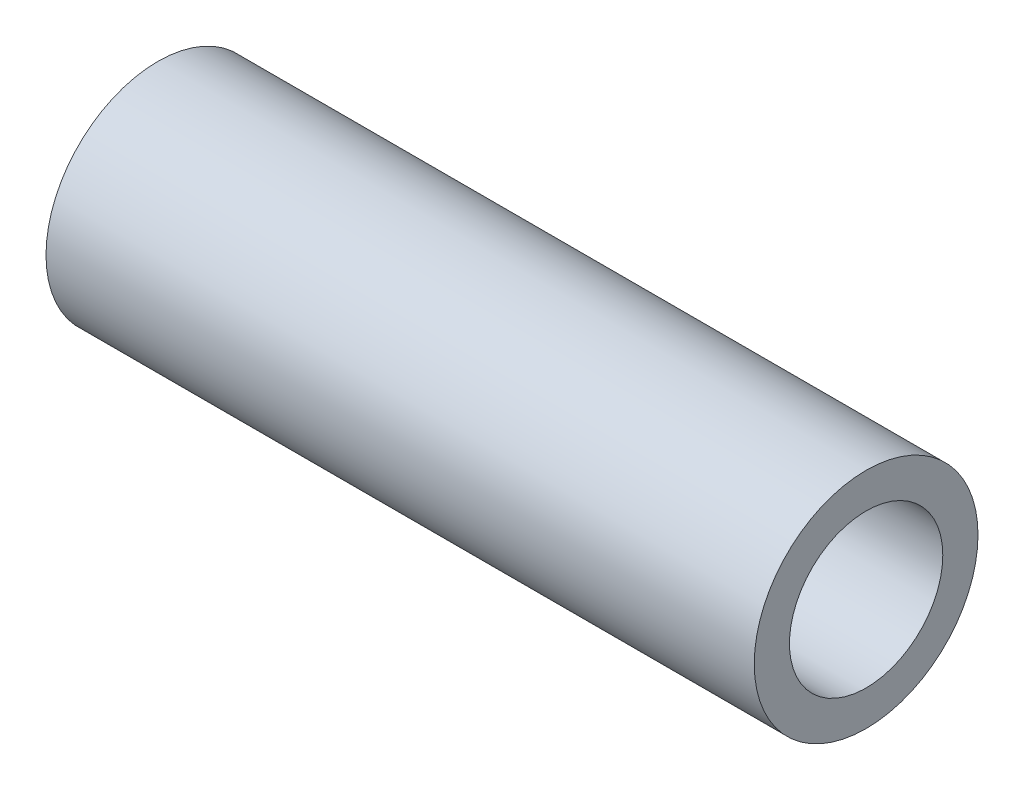
SolidWorks part; units mm, degrees
ref_plane "Front Plane" through (0, 0, 0) normal (0, 0, 1) x (1, 0, 0)
ref_plane "Top Plane" through (0, 0, 0) normal (0, 1, 0) x (1, 0, 0)
ref_plane "Right Plane" through (0, 0, 0) normal (1, 0, 0) x (0, 0, -1)
sketch "Sketch1" plane through (0, 0, 0) normal (1, 0, 0) x (0, 0, -1)
  circle A0 centre (0, 0) radius 4.7625
  circle A1 centre (0, 0) radius 3.2639
  dimension "D1" = 6.5278
  dimension "D2" = 9.525
extrude "Boss-Extrude1" add sketch "Sketch1" along normal blind 30.1498
